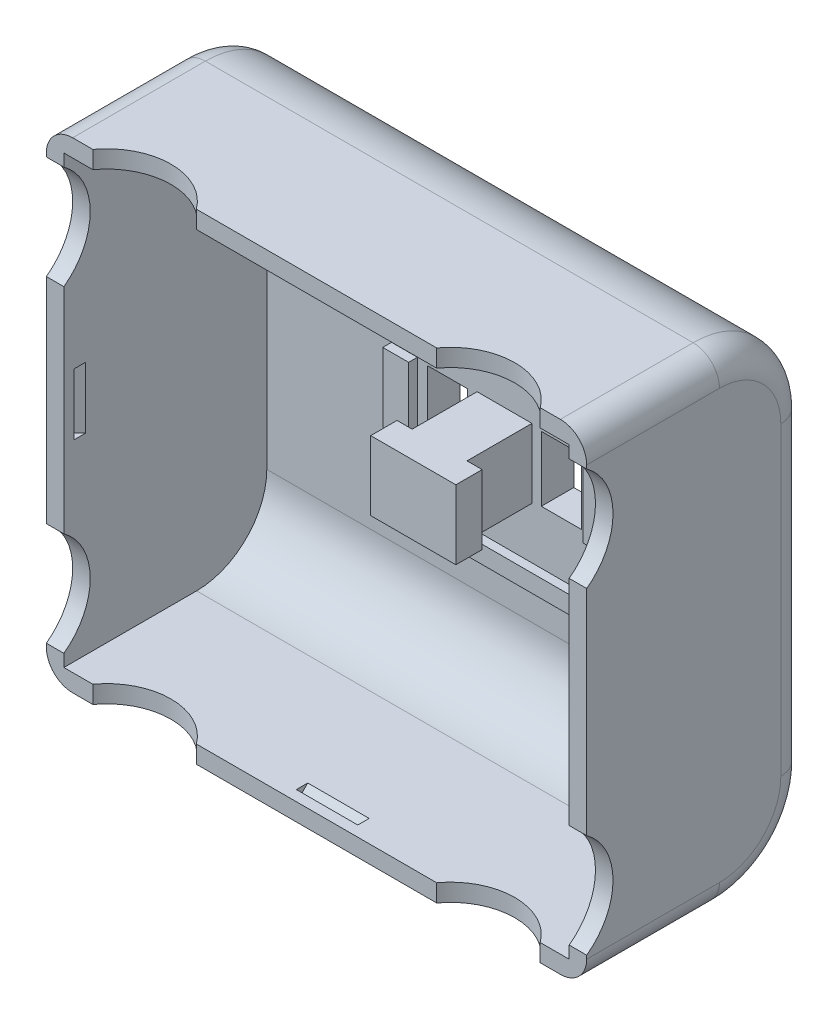
SolidWorks part; units mm, degrees
ref_plane "正面" through (0, 0, 0) normal (0, 0, 1) x (1, 0, 0)
ref_plane "平面" through (0, 0, 0) normal (0, 1, 0) x (1, 0, 0)
ref_plane "右側面" through (0, 0, 0) normal (1, 0, 0) x (0, 0, -1)
sketch "ｽｹｯﾁ1" plane through (0, 0, 0) normal (0, 0, 1) x (1, 0, 0)
  line L0 (0, 0) -> (54, 0) construction
  line L1 (0, 20) -> (54, 20) construction
  line L2 (-1.5, 45.5) -> (55.5, 45.5)
  line L3 (54, 0) -> (54, 40) construction
  line L4 (54, 40) -> (0, 40) construction
  line L5 (0, 40) -> (0, 0) construction
  line L6 (55.5, 45.5) -> (55.5, -5.5)
  line L7 (55.5, -5.5) -> (-1.5, -5.5)
  line L8 (-1.5, -5.5) -> (-1.5, 45.5)
  line L9 (27, 45.5) -> (27, -5.5) construction
  circle A0 centre (2, 2) radius 1.1 construction
  circle A1 centre (52, 2) radius 1.1 construction
  circle A2 centre (52, 38) radius 1.1 construction
  circle A3 centre (2, 38) radius 1.1 construction
  circle A4 centre (2, 38) radius 0.9
  circle A5 centre (2, 38) radius 1.8491
  circle A6 centre (2, 2) radius 1.8491
  circle A7 centre (52, 2) radius 1.8491
  circle A8 centre (52, 38) radius 1.8491
  circle A9 centre (52, 38) radius 0.9
  circle A10 centre (52, 2) radius 0.9
  circle A11 centre (2, 2) radius 0.9
  circle A12 centre (11.0176, 28.1) radius 7
  circle A13 centre (42.9824, 28.1) radius 7
  circle A14 centre (16.5, 8.4) radius 7
  circle A15 centre (37.5, 8.4) radius 7
  dimension "D3" = 2.2
  dimension "D8" = 1.8
  dimension "D9" = 14
  dimension "D10" = 14
  dimension "D11" = 14
  dimension "D12" = 14
  dimension "D1" = 40
  dimension "D2" = 54
  dimension "D4" = 25.5
  dimension "D5" = 25.5
  dimension "D6" = 1.5
  dimension "D7" = 1.5
sketch "ｽｹｯﾁ2" plane through (0, 0, 0) normal (1, 0, 0) x (0, 0, -1)
  line L2 (0, 0) -> (15.13, 0)
  line L3 (0, 0) -> (0, 54.8)
  line L4 (0, 54.8) -> (15.13, 54.8)
  line L5 (25.13, 10) -> (25.13, 44.8)
  arc A0 (15.13, 0) -> (25.13, 10) centre (15.13, 10) ccw
  arc A1 (15.13, 54.8) -> (25.13, 44.8) centre (15.13, 44.8) cw
  point P8 (25.13, 54.8)
  dimension "D3" = 10
  dimension "D1" = 25.13
  dimension "D2" = 54.8
extrude "ﾎﾞｽ - 押し出し1" add sketch "ｽｹｯﾁ2" along normal blind 61.6
shell "ｼｪﾙ1" thickness 2
fillet "ﾌｨﾚｯﾄ2" radius 3 10 edges at (0, 54.8, -7.565) (61.6, 54.8, -7.565) (0, 0, -7.565) (0, 2.9289, -22.2011) (0, 27.4, -25.13) (0, 51.8711, -22.2011) (61.6, 0, -7.565) (61.6, 2.9289, -22.2011) (61.6, 27.4, -25.13) (61.6, 51.8711, -22.2011)
sketch "ｽｹｯﾁ3" plane through (0, 0, -25.13) normal (0, 0, -1) x (-1, 0, 0)
  line L0 (-30.8, 44.8) -> (-30.8, 10) construction
  line L1 (-58.6, 44.8) -> (-3, 44.8) construction
  line L2 (-58.6, 10) -> (-3, 10) construction
  line L3 (-30.8, 39.225) -> (-30.8, 15.575) construction
  line L4 (-24.3025, 31.1) -> (-24.3025, 39.225) construction
  line L5 (-34.9975, 31.1) -> (-34.9975, 23.7)
  line L6 (-26.6025, 31.1) -> (-26.6025, 23.7)
  line L7 (-39.5975, 31.1) -> (-34.9975, 31.1)
  line L8 (-39.5975, 31.1) -> (-39.5975, 23.7)
  line L9 (-39.5975, 23.7) -> (-34.9975, 23.7)
  line L10 (-37.2975, 39.225) -> (-37.2975, 15.575) construction
  line L11 (-22.0025, 23.7) -> (-26.6025, 23.7)
  line L12 (-22.0025, 31.1) -> (-22.0025, 23.7)
  line L13 (-22.0025, 31.1) -> (-26.6025, 31.1)
  line L14 (-30.8, 27.4) -> (-58.6, 27.4) construction
  line L15 (-58.6, 44.8) -> (-58.6, 10) construction
extrude "ｶｯﾄ - 押し出し1" cut sketch "ｽｹｯﾁ3" against normal up to next
sketch "ｽｹｯﾁ4" plane through (0, 0, -23.13) normal (0, 0, 1) x (1, 0, 0)
  line L6 (22.0025, 31.1) -> (26.6025, 31.1) construction
  line L7 (22.0025, 23.7) -> (22.0025, 31.1) construction
  line L8 (22.0025, 23.7) -> (26.6025, 23.7) construction
  line L9 (26.6025, 31.1) -> (26.6025, 23.7) construction
  line L10 (39.5975, 23.7) -> (34.9975, 23.7) construction
  line L11 (34.9975, 31.1) -> (34.9975, 23.7) construction
  line L12 (17.9225, 15.575) -> (30.6725, 15.575)
  line L13 (30.6725, 15.575) -> (43.6775, 15.575)
  line L14 (43.6775, 15.575) -> (43.6775, 39.225)
  line L15 (43.6775, 39.225) -> (30.6725, 39.225)
  line L16 (30.6725, 39.225) -> (17.9225, 39.225)
  line L17 (17.9225, 39.225) -> (17.9225, 15.575)
  line L18 (39.5975, 31.1) -> (34.9975, 31.1) construction
  line L19 (39.5975, 31.1) -> (39.5975, 23.7) construction
  line L20 (22.0025, 31.1) -> (26.6025, 31.1)
  line L21 (22.0025, 23.7) -> (22.0025, 31.1)
  line L22 (22.0025, 23.7) -> (26.6025, 23.7)
  line L23 (26.6025, 31.1) -> (26.6025, 23.7)
  line L24 (39.5975, 23.7) -> (34.9975, 23.7)
  line L25 (34.9975, 31.1) -> (34.9975, 23.7)
  line L26 (39.5975, 31.1) -> (34.9975, 31.1)
  line L27 (39.5975, 31.1) -> (39.5975, 23.7)
extrude "ﾎﾞｽ - 押し出し2" add sketch "ｽｹｯﾁ4" along normal up to vertex (1.7 mm away)
sketch "ｽｹｯﾁ5" plane through (0, 0, -21.43) normal (0, 0, 1) x (1, 0, 0)
  line L9 (20.8725, 31.35) -> (20.8725, 23.45)
  line L10 (17.9225, 31.35) -> (17.9225, 23.45)
  line L11 (43.6775, 31.35) -> (43.6775, 23.45)
  line L12 (40.7275, 23.45) -> (40.7275, 31.35)
  line L13 (43.6775, 37.225) -> (43.6775, 39.225)
  line L14 (43.6775, 39.225) -> (17.9225, 39.225)
  line L15 (17.9225, 37.225) -> (43.6775, 37.225)
  line L16 (43.6775, 17.575) -> (17.9225, 17.575)
  line L17 (17.9225, 15.575) -> (43.6775, 15.575)
  line L18 (17.9225, 31.35) -> (20.8725, 31.35)
  line L19 (17.9225, 23.45) -> (20.8725, 23.45)
  line L20 (40.7275, 31.35) -> (43.6775, 31.35)
  line L21 (40.7275, 23.45) -> (43.6775, 23.45)
  line L22 (17.9225, 39.225) -> (17.9225, 37.225)
  line L23 (17.9225, 17.575) -> (17.9225, 15.575)
  line L24 (43.6775, 17.575) -> (43.6775, 15.575)
extrude "ﾎﾞｽ - 押し出し3" add sketch "ｽｹｯﾁ5" along normal up to vertex (1 mm away)
ref_plane "平面1" through (-6.5183, 23.4524, -44.2238) normal (0, 1, 0) x (1, 0, 0)
sketch "ｽｹｯﾁ6" plane through (-6.5183, 23.4524, -44.2238) normal (0, 1, 0) x (1, 0, 0)
  line L0 (34.1908, -22.7938) -> (40.4458, -22.7938)
  line L1 (40.4458, -22.7938) -> (40.4458, -30.1938)
  line L2 (40.4458, -30.1938) -> (42.1708, -30.1938)
  line L3 (42.1708, -30.1938) -> (42.1708, -33.1938)
  line L4 (42.1708, -33.1938) -> (32.4658, -33.1938)
  line L5 (32.4658, -33.1938) -> (32.4658, -30.1938)
  line L6 (32.4658, -30.1938) -> (34.1908, -30.1938)
  line L7 (34.1908, -30.1938) -> (34.1908, -22.7938)
extrude "ﾎﾞｽ - 押し出し4" add sketch "ｽｹｯﾁ6" along normal up to vertex (7.8976 mm away)
sketch "ｽｹｯﾁ8" plane through (0, 0, 0) normal (-1, 0, 0) x (0, 0, 1)
  line L0 (0, 51.8) -> (0, 3) construction
  line L1 (0, 51.3992) -> (0, 39.6008)
  line L2 (0, 15.1992) -> (0, 3.4008)
  arc A0 (0, 51.3992) -> (0, 39.6008) centre (4.3, 45.5) ccw
  arc A1 (0, 15.1992) -> (0, 3.4008) centre (4.3, 9.3) ccw
extrude "ｶｯﾄ - 押し出し3" cut sketch "ｽｹｯﾁ8" against normal up to vertex
sketch "ｽｹｯﾁ9" plane through (0, 0, 0) normal (0, -1, 0) x (1, 0, 0)
  line L0 (58.6, 0) -> (3, 0) construction
  line L1 (56.2992, 0) -> (44.5008, 0)
  line L2 (17.0992, 0) -> (5.3008, 0)
  arc A0 (44.5008, 0) -> (56.2992, 0) centre (50.4, 4.3) ccw
  arc A1 (5.3008, 0) -> (17.0992, 0) centre (11.2, 4.3) ccw
extrude "ｶｯﾄ - 押し出し4" cut sketch "ｽｹｯﾁ9" against normal up to vertex
ref_plane "平面2" through (0, 27.4, 0) normal (0, -1, 0) x (-1, 0, 0)
sketch "ｽｹｯﾁ11" plane through (0, 27.4, 0) normal (0, -1, 0) x (-1, 0, 0)
  line L0 (-59.6, 0) -> (-59.6, 15.13) construction
  line L1 (-59.6, 1.1766) -> (-59.6, 2.4767)
  line L2 (-59.6, 2.3353) -> (-60.1887, 1.7466) construction
  line L3 (-60.1887, 1.7466) -> (-60.1887, 1.2766) construction
  line L4 (-60.1887, 1.2766) -> (-59.6, 1.2766) construction
  line L5 (-60.2887, 1.788) -> (-59.6, 2.4767)
  line L6 (-60.2887, 1.788) -> (-60.2887, 1.1766)
  line L7 (-60.2887, 1.1766) -> (-59.6, 1.1766)
  line L8 (-59.6707, 2.406) -> (-60.2887, 1.788) construction
  line L9 (-30.8, 25.13) -> (-30.8, 48.4859) construction
  line L10 (-58.6, 25.13) -> (-3, 25.13) construction
  line L11 (-1.4113, 1.7466) -> (-1.4113, 1.2766) construction
  line L12 (-2, 2.3353) -> (-1.4113, 1.7466) construction
  line L13 (-1.3113, 1.1766) -> (-2, 1.1766)
  line L14 (-1.3113, 1.788) -> (-1.3113, 1.1766)
  line L15 (-1.3113, 1.788) -> (-2, 2.4767)
  line L16 (-1.4113, 1.2766) -> (-2, 1.2766) construction
  line L17 (-2, 1.1766) -> (-2, 2.4767)
  dimension "D1" = 0.1
  dimension "D2" = 0
extrude "ｶｯﾄ - 押し出し5" cut sketch "ｽｹｯﾁ11" against normal mid plane 7
ref_plane "平面3" through (30.8, 0, 0) normal (1, 0, 0) x (0, 0, -1)
sketch "ｽｹｯﾁ12" plane through (30.8, 0, 0) normal (1, 0, 0) x (0, 0, -1)
  line L0 (1.7713, 1.4113) -> (1.3013, 1.4113) construction
  line L1 (2.36, 2) -> (1.7713, 1.4113) construction
  line L2 (2.5014, 2) -> (1.2013, 2)
  line L3 (2.36, 52.8) -> (1.7713, 53.3887) construction
  line L4 (1.7713, 53.3887) -> (1.3013, 53.3887) construction
  line L5 (1.3013, 53.3887) -> (1.3013, 52.8) construction
  line L6 (1.8128, 53.4887) -> (2.5014, 52.8)
  line L7 (1.8128, 53.4887) -> (1.2013, 53.4887)
  line L8 (1.2013, 53.4887) -> (1.2013, 52.8)
  line L9 (2.4307, 52.8707) -> (1.8128, 53.4887) construction
  line L10 (15.13, 52.8) -> (0, 52.8) construction
  line L11 (2.5014, 52.8) -> (1.2013, 52.8)
  line L12 (25.13, 27.4) -> (38.8234, 27.4) construction
  line L13 (25.13, 44.8) -> (25.13, 10) construction
  line L14 (1.2013, 1.3113) -> (1.2013, 2)
  line L15 (1.8128, 1.3113) -> (1.2013, 1.3113)
  line L16 (1.8128, 1.3113) -> (2.5014, 2)
  dimension "D2" = 0
  dimension "D1" = 0.1
extrude "ｶｯﾄ - 押し出し6" cut sketch "ｽｹｯﾁ12" against normal mid plane 7
